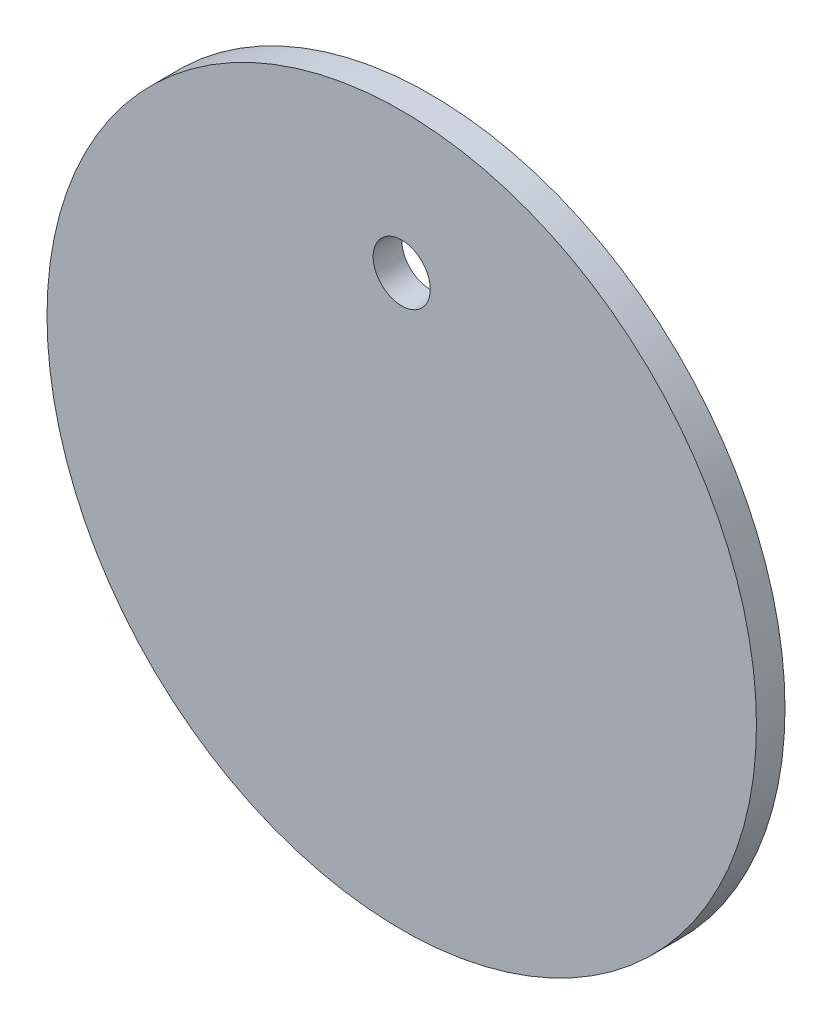
SolidWorks part; units mm, degrees
ref_plane "Front Plane" through (0, 0, 0) normal (0, 0, 1) x (1, 0, 0)
ref_plane "Top Plane" through (0, 0, 0) normal (0, 1, 0) x (1, 0, 0)
ref_plane "Right Plane" through (0, 0, 0) normal (1, 0, 0) x (0, 0, -1)
sketch "Sketch2" plane through (0, 0, 0) normal (0, 0, 1) x (1, 0, 0)
  circle A0 centre (0, 0) radius 24.85
  dimension "D1" = 49.7
extrude "Boss-Extrude1" add sketch "Sketch2" along normal blind 2
sketch "Sketch3" plane through (0, 0, 2) normal (0, 0, 1) x (1, 0, 0)
  circle A0 centre (0, 15) radius 2
  dimension "D1" = 4
  dimension "D2" = 15
extrude "Cut-Extrude2" cut sketch "Sketch3" against normal blind 2
